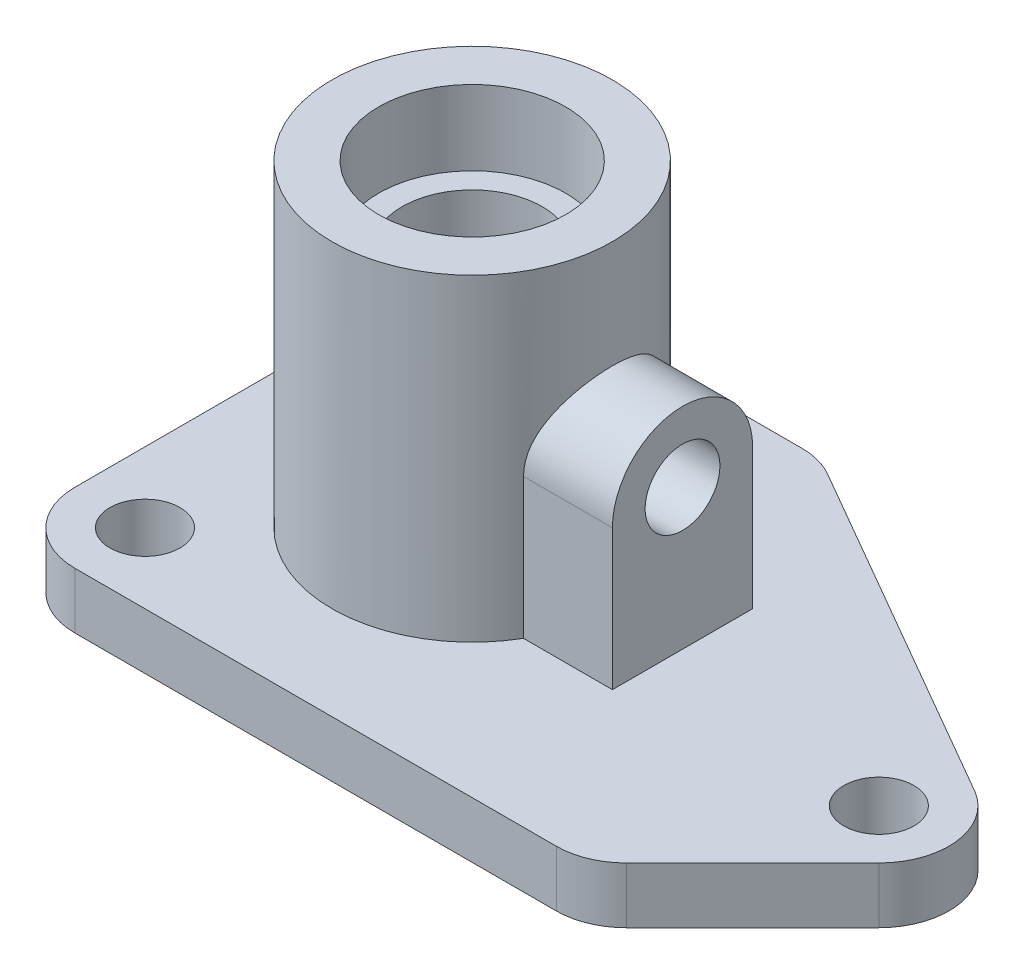
SolidWorks part; units mm, degrees
ref_plane "Front Plane" through (0, 0, 0) normal (0, 0, 1) x (1, 0, 0)
ref_plane "Top Plane" through (0, 0, 0) normal (0, 1, 0) x (1, 0, 0)
ref_plane "Right Plane" through (0, 0, 0) normal (1, 0, 0) x (0, 0, -1)
sketch "Sketch1" plane through (0, 0, 0) normal (0, 1, 0) x (1, 0, 0)
  line L0 (-50, 35) -> (-50, -35)
  line L1 (-35, -50) -> (68, -50)
  line L2 (78.6066, -45.6066) -> (105.6066, -18.6066)
  line L3 (-35, 50) -> (20.5218, 50)
  line L4 (28.0218, 47.9904) -> (102.5, 4.9904)
  circle A0 centre (95, -8) radius 7.5
  arc A1 (105.6066, -18.6066) -> (102.5, 4.9904) centre (95, -8) ccw
  arc A3 (68, -50) -> (78.6066, -45.6066) centre (68, -35) ccw
  arc A4 (20.5218, 50) -> (28.0218, 47.9904) centre (20.5218, 35) cw
  arc A5 (-50, -35) -> (-35, -50) centre (-35, -35) ccw
  arc A6 (-50, 35) -> (-35, 50) centre (-35, 35) cw
  circle A7 centre (-35, 35) radius 7.5
  circle A8 centre (-35, -35) radius 7.5
  point P15 (-50, -50)
  point P19 (-50, 50)
  point P22 (-35, -32.2254)
  dimension "D1" = 50
  dimension "D6" = 15
  dimension "D7" = 30
  dimension "D10" = 15
  dimension "D11" = 15
  dimension "D12" = 15
  dimension "D2" = 50
  dimension "D3" = 145
  dimension "D4" = 135
  dimension "D5" = 100
  dimension "D8" = 42
  dimension "D9" = 30
extrude "Boss-Extrude1" add sketch "Sketch1" along normal blind 12
sketch "Sketch3" plane through (0, 12, 0) normal (0, 1, 0) x (1, 0, 0)
  circle A0 centre (0, 0) radius 30
  dimension "D1" = 60
extrude "Boss-Extrude2" add sketch "Sketch3" along normal blind 68 contours A0
hole_wizard "Hole1" positions "Sketch4" profile "Sketch6" legacy end condition through all
sketch "Sketch4" plane through (0, 80, 0) normal (0, 1, 0) x (1, 0, 0)
  point P0 (0, 0)
sketch "Sketch6" plane through (0, 80, 0) normal (1, 0, 0) x (0, 0, 1)
  line L0 (0, 0) -> (0, 89.0129)
  line L1 (0, 89.0129) -> (15, 80)
  line L2 (15, 80) -> (15, 16)
  line L3 (15, 16) -> (20, 16)
  line L4 (20, 0) -> (0, 0)
  line L5 (0, -11.3109) -> (0, 121.1557) construction
  line L6 (0, 89.0129) -> (-15, 80) construction
  line L7 (20, 16) -> (20, 0)
  dimension "Depth" = 80
  dimension "Drill Angle" = 118
  dimension "Diameter" = 30
  dimension "C-Bore Diameter" = 40
  dimension "C-Bore Depth" = 16
ref_plane "Plane1" through (45, 0, 0) normal (1, 0, 0) x (0, 0, -1)
sketch "Sketch10" plane through (45, 0, 0) normal (1, 0, 0) x (0, 0, -1)
  line L0 (0, 0) -> (0, 42) construction
  line L1 (-15, 42) -> (-15, 12)
  line L2 (-15, 12) -> (15, 12)
  line L3 (15, 42) -> (15, 12)
  line L4 (4.9904, 12) -> (47.9904, 12) construction
  line L5 (4.9904, 12) -> (-18.6066, 12) construction
  arc A0 (15, 42) -> (-15, 42) centre (0, 42) ccw
  point P3 (0, 12)
  dimension "R2" = 30
  dimension "D1" = 42
extrude "Boss-Extrude3" add sketch "Sketch10" against normal up to surface (19.0192 mm away) contours L1 L2 L3 A0
sketch "Sketch11" plane through (45, 0, 0) normal (1, 0, 0) x (0, 0, -1)
  circle A0 centre (0, 42) radius 8
  arc A1 (15, 42) -> (-15, 42) centre (0, 42) ccw construction
  point P2 (0, 42.9769)
  dimension "D1" = 16
extrude "Cut-Extrude1" cut sketch "Sketch11" against normal up to surface (32.3114 mm away) contours A0
